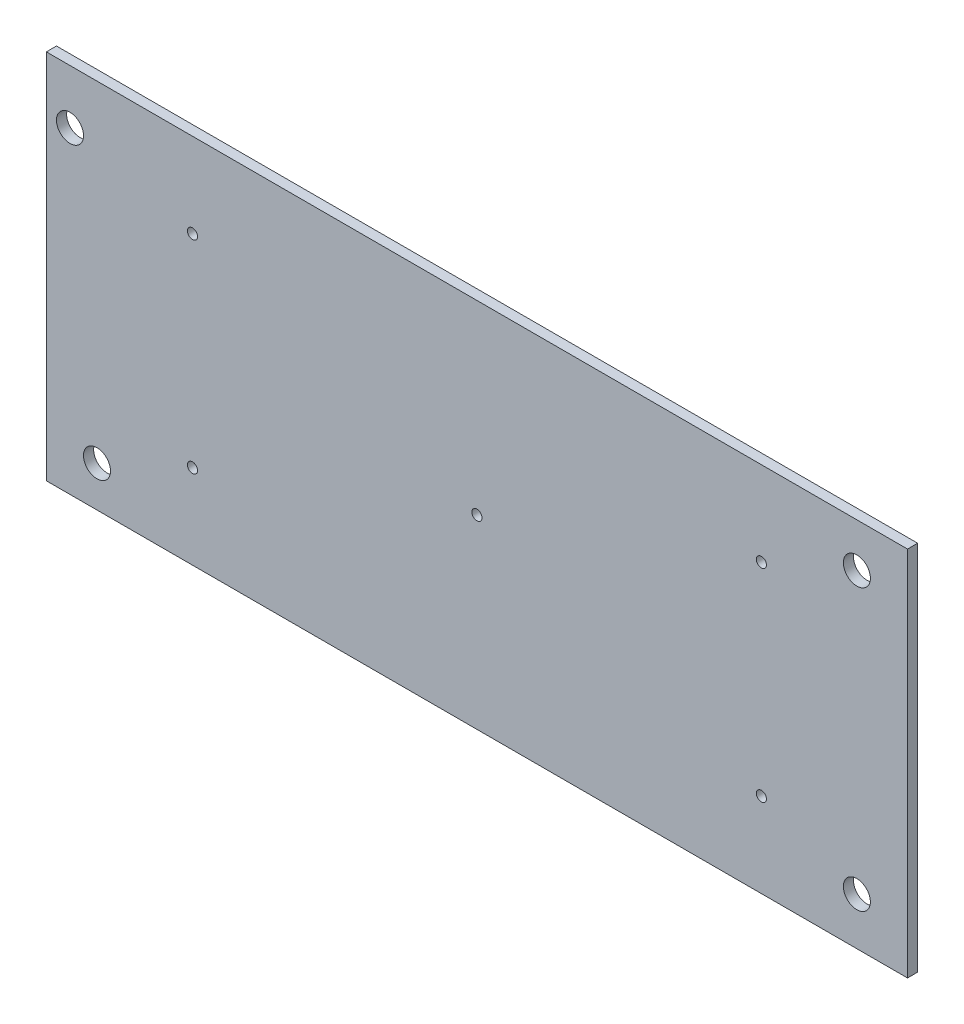
SolidWorks part; units mm, degrees
ref_plane "Front Plane" through (0, 0, 0) normal (0, 0, 1) x (1, 0, 0)
ref_plane "Top Plane" through (0, 0, 0) normal (0, 1, 0) x (1, 0, 0)
ref_plane "Right Plane" through (0, 0, 0) normal (1, 0, 0) x (0, 0, -1)
sketch "Sketch1" plane through (0, 0, 0) normal (0, 0, 1) x (1, 0, 0)
  line L0 (-140.6364, 23.6818) -> (114.3636, 23.6818) construction
  line L1 (-140.6364, 48.6818) -> (114.3636, 48.6818)
  line L2 (-140.6364, 48.6818) -> (-140.6364, -61.3182)
  line L3 (-140.6364, -61.3182) -> (114.3636, -61.3182)
  line L4 (114.3636, 48.6818) -> (114.3636, -61.3182)
  line L5 (-140.6364, -6.3182) -> (114.3636, -6.3182) construction
  line L6 (-140.6364, -36.3182) -> (114.3636, -36.3182) construction
  line L7 (-13.1364, 48.6818) -> (-13.1364, -61.3182) construction
  circle A0 centre (-125.6364, -49.3182) radius 4
  circle A1 centre (-133.6364, 32.6818) radius 4
  circle A2 centre (99.3636, -47.3182) radius 4
  circle A3 centre (99.3636, 35.6818) radius 4
  circle A4 centre (-97.3692, 23.6818) radius 1.5
  circle A5 centre (-97.3692, -36.3182) radius 1.5
  circle A6 centre (71.0965, -36.3182) radius 1.5
  circle A7 centre (71.0965, 23.6818) radius 1.5
  circle A8 centre (-13.1364, -6.3182) radius 1.5
  dimension "D11" = 8
  dimension "D12" = 8
  dimension "D13" = 8
  dimension "D14" = 8
  dimension "D16" = 3
  dimension "D17" = 3
  dimension "D18" = 3
  dimension "D1" = 255
  dimension "D2" = 110
  dimension "D3" = 240
  dimension "D4" = 248
  dimension "D5" = 15
  dimension "D6" = 15
  dimension "D7" = 16
  dimension "D8" = 12
  dimension "D9" = 14
  dimension "D10" = 13
  dimension "D15" = 30
extrude "Boss-Extrude1" add sketch "Sketch1" along normal blind 3
